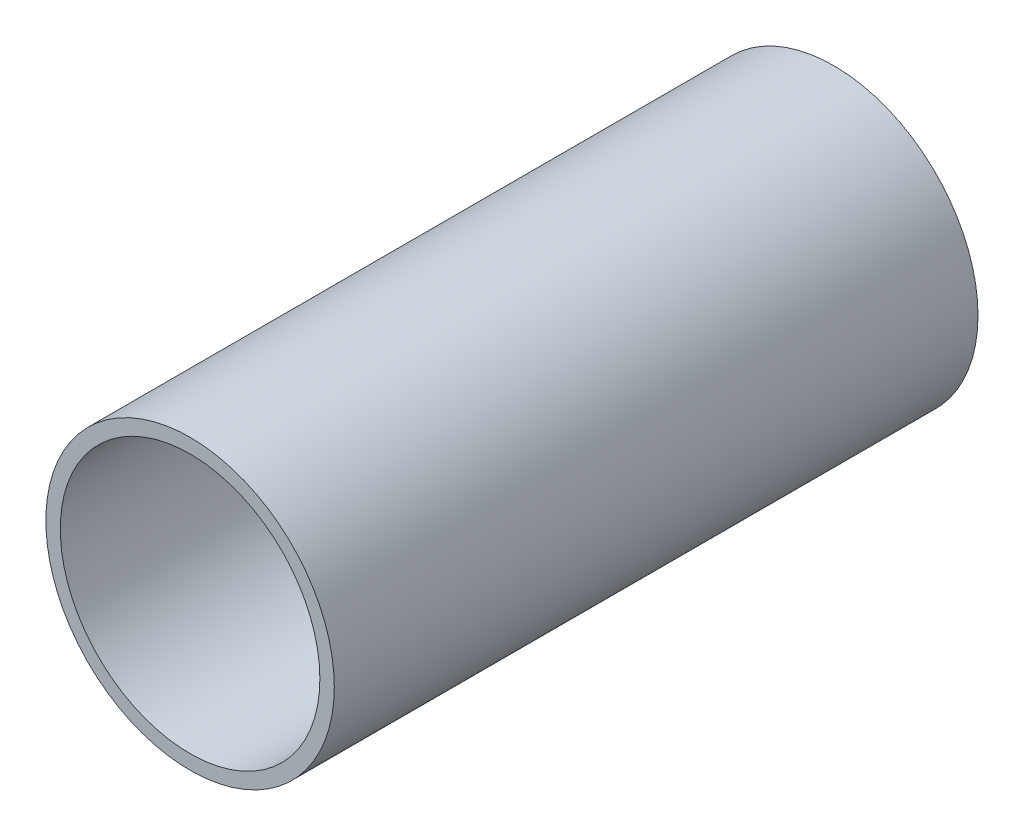
SolidWorks part; units mm, degrees
ref_plane "Front Plane" through (0, 0, 0) normal (0, 0, 1) x (1, 0, 0)
ref_plane "Top Plane" through (0, 0, 0) normal (0, 1, 0) x (1, 0, 0)
ref_plane "Right Plane" through (0, 0, 0) normal (1, 0, 0) x (0, 0, -1)
sketch "Sketch1" plane through (0, 0, 0) normal (0, 0, 1) x (1, 0, 0)
  circle A0 centre (0, 0) radius 18
  circle A1 centre (0, 0) radius 20
  dimension "D1" = 36
  dimension "D2" = 40
extrude "Boss-Extrude1" add sketch "Sketch1" along normal blind 89.2635
